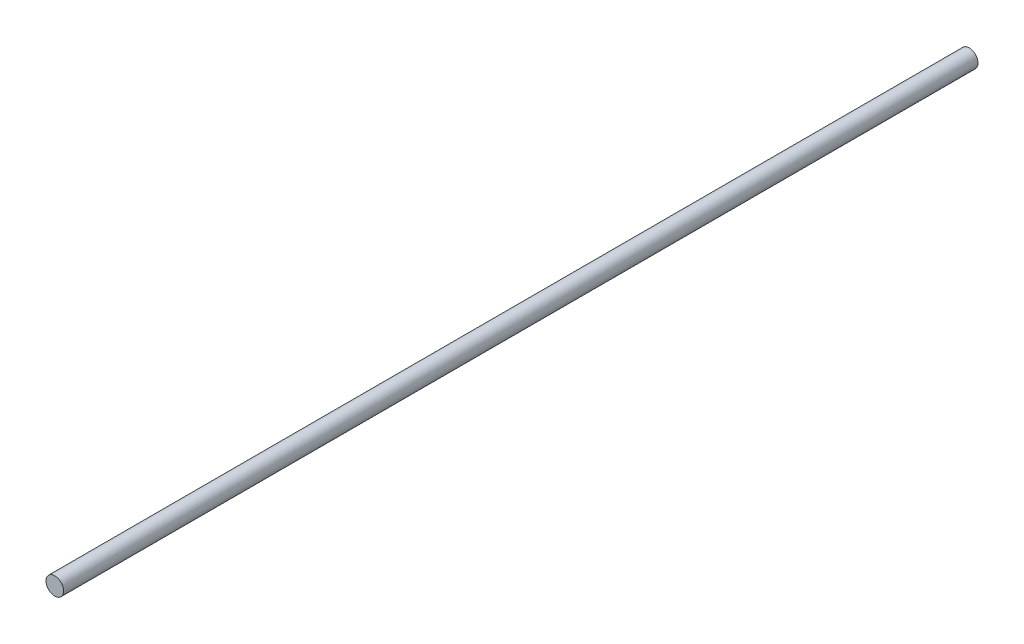
SolidWorks part; units mm, degrees
ref_plane "Front Plane" through (0, 0, 0) normal (0, 0, 1) x (1, 0, 0)
ref_plane "Top Plane" through (0, 0, 0) normal (0, 1, 0) x (1, 0, 0)
ref_plane "Right Plane" through (0, 0, 0) normal (1, 0, 0) x (0, 0, -1)
sketch "Sketch1" plane through (0, 0, 0) normal (0, 0, 1) x (1, 0, 0)
  circle A0 centre (0, 0) radius 4
  dimension "D1" = 8
extrude "Boss-Extrude1" add sketch "Sketch1" along normal blind 415
